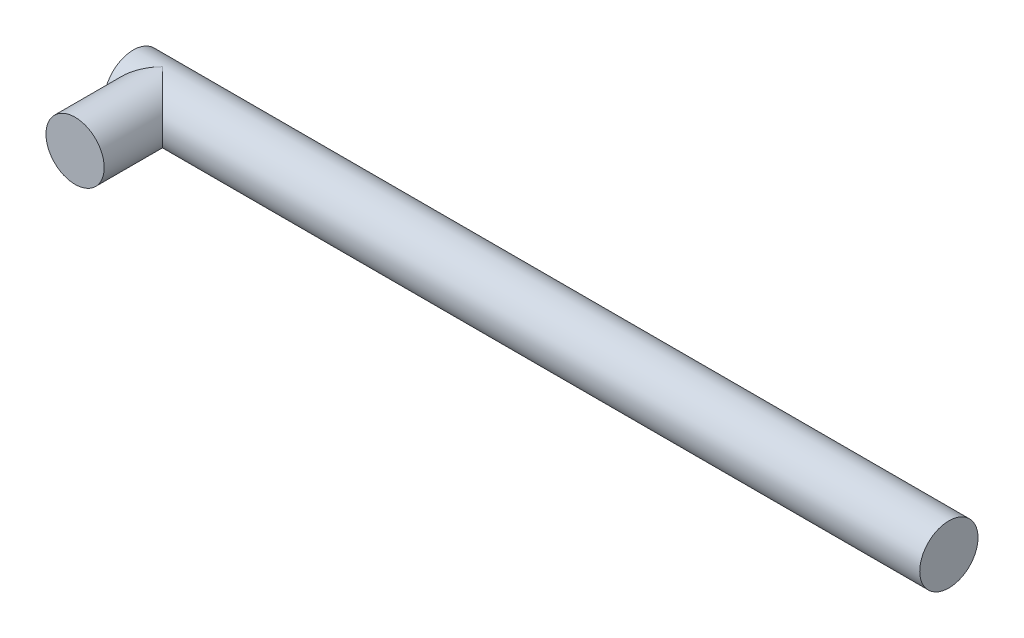
SolidWorks part; units mm, degrees
ref_plane "Front Plane" through (0, 0, 0) normal (0, 0, 1) x (1, 0, 0)
ref_plane "Top Plane" through (0, 0, 0) normal (0, 1, 0) x (1, 0, 0)
ref_plane "Right Plane" through (0, 0, 0) normal (1, 0, 0) x (0, 0, -1)
sketch "Sketch1" plane through (0, 0, 0) normal (1, 0, 0) x (0, 0, -1)
  circle A0 centre (0, 0) radius 250
  dimension "D1" = 500
extrude "Boss-Extrude1" add sketch "Sketch1" along normal blind 7000
sketch "Sketch2" plane through (0, 0, 0) normal (0, 0, 1) x (1, 0, 0)
  line L0 (0, 250) -> (0, -250) construction
  circle A0 centre (250, 0) radius 250
  dimension "D1" = 500
extrude "Boss-Extrude2" add sketch "Sketch2" along normal blind 750
